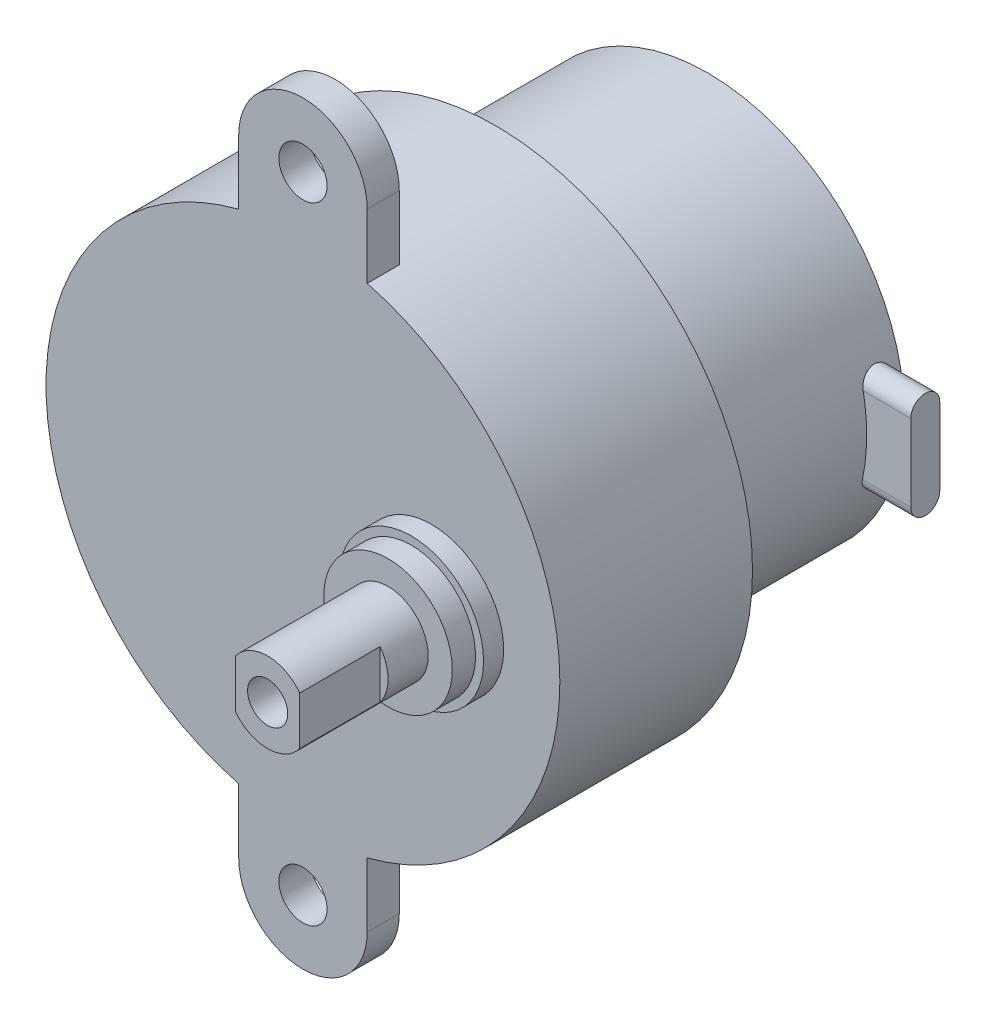
SolidWorks part; units mm, degrees
ref_plane "前视基准面" through (0, 0, 0) normal (0, 0, 1) x (1, 0, 0)
ref_plane "上视基准面" through (0, 0, 0) normal (0, 1, 0) x (1, 0, 0)
ref_plane "右视基准面" through (0, 0, 0) normal (1, 0, 0) x (0, 0, -1)
sketch "草图1" plane through (0, 0, 0) normal (0, 0, 1) x (1, 0, 0)
  circle A0 centre (0, 0) radius 16
  dimension "D1" = 32
extrude "凸台-拉伸1" add sketch "草图1" against normal blind 12
sketch "草图2" plane through (0, 0, -12) normal (0, 0, -1) x (-1, 0, 0)
  circle A0 centre (0, 0) radius 13
  dimension "D1" = 26
extrude "凸台-拉伸2" add sketch "草图2" along normal blind 2
sketch "草图3" plane through (0, 0, -14) normal (0, 0, -1) x (-1, 0, 0)
  circle A0 centre (0, 0) radius 12.25
  dimension "D1" = 24.5
extrude "凸台-拉伸4" add sketch "草图3" along normal offset from surface (11.2 mm away) 25.2 up to face at (16, 0, 0)
sketch "草图4" plane through (0, 0, 0) normal (0, 0, 1) x (1, 0, 0)
  line L0 (0, 25.1284) -> (0, -17.8912) construction
  line L1 (-18.3367, 0) -> (17.406, 0) construction
  line L2 (-4, 19.5) -> (-4, 15.4919)
  line L3 (4, 19.5) -> (4, 15.4919)
  line L4 (-4, -15.4919) -> (-4, -19.5)
  line L5 (4, -15.4919) -> (4, -19.5)
  circle A0 centre (0, 19.5) radius 1.5
  circle A1 centre (0, -19.5) radius 1.5
  arc A2 (4, 19.5) -> (-4, 19.5) centre (0, 19.5) ccw
  arc A3 (4, -19.5) -> (-4, -19.5) centre (0, -19.5) cw
  arc A4 (4, 15.4919) -> (-4, 15.4919) centre (0, 0) ccw
  circle A5 centre (0, 0) radius 16
  arc A6 (-4, -15.4919) -> (4, -15.4919) centre (0, 0) ccw
  point P13 (-4, -19.2869)
  dimension "D2" = 3
  dimension "D1" = 8
  dimension "D3" = 39
  dimension "D4" = 0
extrude "凸台-拉伸5" add sketch "草图4" against normal blind 2
sketch "草图17" plane through (0, 0, 0) normal (0, 1, 0) x (1, 0, 0)
  line L0 (-19.9293, 0) -> (18.6721, 0) construction
  line L1 (8, -7.0266) -> (8, 4.8937) construction
  line L2 (8, -10.2) -> (8, 0)
  line L3 (3.5, 0) -> (3.5, -1.25)
  line L4 (3.5, -1.25) -> (4, -1.25)
  line L5 (4, -1.25) -> (4, -2.7)
  line L6 (4, -2.7) -> (5.5, -2.7)
  line L7 (5.5, -2.7) -> (5.5, -10.2)
  line L8 (5.5, -10.2) -> (8, -10.2)
  line L9 (8, -10.2) -> (8, 0) construction
  line L10 (8, 0) -> (3.5, 0)
  line L11 (6, -10.2) -> (6, -5.2) construction
  line L12 (10, -10.2) -> (10, -5.2) construction
  line L13 (6, -5.2) -> (10, -5.2) construction
  point P17 (0, 0)
  point P18 (0, 0)
  dimension "D1" = 8
  dimension "D2" = 4.5
  dimension "D3" = 2.7
  dimension "D4" = 1.25
  dimension "D5" = 4
  dimension "D6" = 2.5
  dimension "D7" = 10.2
  dimension "D8" = 4
  dimension "D9" = 5
revolve "旋转1" add sketch "草图17" angle 360 about L2
sketch "草图21" plane through (0, 0, 10.2) normal (0, 0, 1) x (1, 0, 0)
  line L0 (12.9799, 0) -> (1.0079, 0) construction
  line L1 (8, -2.9145) -> (8, 2.8824) construction
  line L2 (6, 2.4202) -> (6, -2.6308)
  line L3 (10.599, 2.4202) -> (10.599, -2.6308)
  line L4 (6, 2.4202) -> (5.401, 2.4202)
  line L5 (5.401, 2.4202) -> (5.401, -2.6308)
  line L6 (5.401, -2.6308) -> (6, -2.6308)
  line L7 (10, 2.4202) -> (10.599, 2.4202)
  line L8 (10, 2.4202) -> (10, -2.6308)
  line L9 (10.599, -2.6308) -> (10, -2.6308)
  circle A0 centre (8, 0) radius 2.5 construction
  circle A1 centre (8, 0) radius 2.5
  dimension "D1" = 4
extrude "切除-拉伸2" cut sketch "草图21" against normal blind 5 contours L4 L5 L6 L2 | L7 L3 L9 L8
hole_wizard "M3 螺纹孔1" positions "草图23" profile "草图24" tap size "M3" standard "GB"
sketch "草图23" plane through (0, 0, 10.2) normal (0, 0, 1) x (1, 0, 0)
  point P0 (8, 0)
cosmetic thread "孔螺蚊线1" parameters "D1"=6, "D2"=3
sketch "草图24" plane through (8, 0, 10.2) normal (1, 0, 0) x (0, -1, 0)
  line L0 (0, 0) -> (0, 8.2511)
  line L1 (0, 8.2511) -> (1.25, 7.5)
  line L2 (1.25, 7.5) -> (1.25, 0)
  line L5 (1.25, 0) -> (0, 0)
  line L10 (0, 8.2511) -> (-1.25, 7.5) construction
  line L11 (0, -6.35) -> (0, 107.95) construction
  dimension "螺纹孔钻头直径" = 2.5
  dimension "螺纹孔钻头深度" = 7.5
  dimension "导头角度" = 118
sketch "草图25" plane through (0, 0, 0) normal (1, 0, 0) x (0, 0, -1)
  line L0 (23.7581, 2.2831) -> (23.7581, -2.5158) construction
  line L1 (24.6597, 2.2831) -> (24.6597, -2.5158)
  line L2 (22.8565, 2.2831) -> (22.8565, -2.5158)
  arc A0 (24.6597, 2.2831) -> (22.8565, 2.2831) centre (23.7581, 2.2831) ccw
  arc A1 (22.8565, -2.5158) -> (24.6597, -2.5158) centre (23.7581, -2.5158) ccw
  point P2 (23.7581, -0.1163)
extrude "凸台-拉伸16" add sketch "草图25" along normal blind 15
